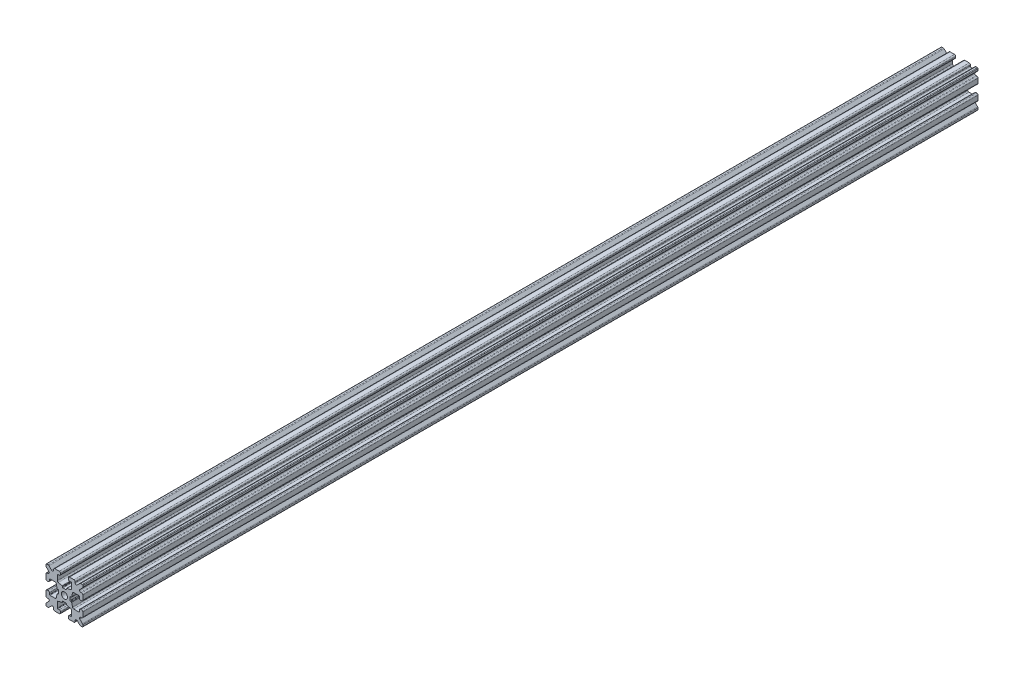
SolidWorks part; units mm, degrees
material "1060 Alloy"
ref_plane "Front Plane" through (0, 0, 0) normal (0, 0, 1) x (1, 0, 0)
ref_plane "Top Plane" through (0, 0, 0) normal (0, 1, 0) x (1, 0, 0)
ref_plane "Right Plane" through (0, 0, 0) normal (1, 0, 0) x (0, 0, -1)
sketch "Sketch1" plane through (0, 0, 0) normal (0, 0, 1) x (1, 0, 0)
  line L1 (-7.5, -7.5) -> (7.5, -7.5)
  line L2 (-7.5, -7.5) -> (-7.5, 7.5)
  line L3 (-7.5, 7.5) -> (7.5, 7.5)
  line L4 (7.5, -7.5) -> (7.5, 7.5)
  line L5 (-7.5, -7.5) -> (7.5, 7.5) construction
  line L6 (-7.5, 7.5) -> (7.5, -7.5) construction
  circle A0 centre (0, 0) radius 1.25
  point P0 (0, 0)
  dimension "D2" = 2.5
  dimension "D1" = 15
extrude "Boss-Extrude1" add sketch "Sketch1" along normal mid plane 365
fillet "Fillet1" radius 0.25 4 edges at (7.5, -7.5, 0) (-7.5, -7.5, 0) (7.5, 7.5, 0) (-7.5, 7.5, 0)
sketch "Sketch2" plane through (0, 0, 182.5) normal (0, 0, 1) x (1, 0, 0)
  line L0 (-7.5, 7.25) -> (-7.5, -7.25) construction
  line L1 (-7.5, 1.6) -> (-6.1, 1.6)
  line L2 (-7.5, 1.6) -> (-7.5, -1.6)
  line L3 (-7.5, -1.6) -> (-6.1, -1.6)
  line L4 (-6.1, 1.6) -> (-6.1, 2.9)
  line L5 (0, 0) -> (-12.1036, 0) construction
  line L6 (-6.1, -2.9) -> (-3.4, -2.9)
  line L7 (0, 0) -> (-7.25, 7.25) construction
  line L8 (-6.1, 2.9) -> (-3.4, 2.9)
  line L9 (-3.4, -2.9) -> (-3.4, 2.9)
  line L10 (55, 0) -> (-55, 0) construction
  line L11 (-6.1, -2.9) -> (-6.1, -1.6)
  line L12 (2.9, 6.1) -> (1.6, 6.1)
  line L13 (2.9, 3.4) -> (-2.9, 3.4)
  line L14 (-2.9, 6.1) -> (-2.9, 3.4)
  line L15 (2.9, 6.1) -> (2.9, 3.4)
  line L16 (-1.6, 6.1) -> (-2.9, 6.1)
  line L17 (1.6, 7.5) -> (1.6, 6.1)
  line L18 (-1.6, 7.5) -> (1.6, 7.5)
  line L19 (-1.6, 7.5) -> (-1.6, 6.1)
  line L20 (-1.6, -7.5) -> (-1.6, -6.1)
  line L21 (-1.6, -7.5) -> (1.6, -7.5)
  line L22 (1.6, -7.5) -> (1.6, -6.1)
  line L23 (-1.6, -6.1) -> (-2.9, -6.1)
  line L24 (2.9, -6.1) -> (2.9, -3.4)
  line L25 (-2.9, -6.1) -> (-2.9, -3.4)
  line L26 (2.9, -3.4) -> (-2.9, -3.4)
  line L27 (2.9, -6.1) -> (1.6, -6.1)
  line L28 (6.1, -2.9) -> (6.1, -1.6)
  line L29 (3.4, -2.9) -> (3.4, 2.9)
  line L30 (6.1, 2.9) -> (3.4, 2.9)
  line L31 (6.1, -2.9) -> (3.4, -2.9)
  line L32 (6.1, 1.6) -> (6.1, 2.9)
  line L33 (7.5, -1.6) -> (6.1, -1.6)
  line L34 (7.5, 1.6) -> (7.5, -1.6)
  line L35 (7.5, 1.6) -> (6.1, 1.6)
  dimension "D1" = 3.2
  dimension "D2" = 5.8
  dimension "D3" = 1.4
  dimension "D4" = 2.7
extrude "Cut-Extrude1" cut sketch "Sketch2" against normal through all
sketch "Sketch4" plane through (0, 0, 182.5) normal (0, 0, 1) x (1, 0, 0)
  line L0 (-3.4, 2.9) -> (-2.75, 0)
  line L1 (55, 0) -> (-55, 0) construction
  line L2 (-2.75, 0) -> (-3.4, -2.9)
  line L3 (-3.4, -2.9) -> (-3.4, 2.9) construction
  line L4 (-3.4, 2.9) -> (-3.4, -2.9)
  line L5 (-2.9, 3.4) -> (0, 2.75)
  line L6 (0, 2.75) -> (2.9, 3.4)
  line L7 (2.9, 3.4) -> (-2.9, 3.4)
  line L8 (3.4, 2.9) -> (2.75, 0)
  line L9 (2.75, 0) -> (3.4, -2.9)
  line L10 (3.4, -2.9) -> (3.4, 2.9)
  line L11 (-2.9, -3.4) -> (0, -2.75)
  line L12 (0, -2.75) -> (2.9, -3.4)
  line L13 (2.9, -3.4) -> (-2.9, -3.4)
  circle A2 centre (0, 0) radius 2.75
  circle A3 centre (0, 0) radius 2.75 construction
  dimension "D1" = 1.5
extrude "Cut-Extrude3" cut sketch "Sketch4" against normal through all
fillet "Fillet3" radius 0.5 16 edges at (-6.1, -1.6, 0) (-7.5, -1.6, 0) (-6.1, 1.6, 0) (-7.5, 1.6, 0) (-1.6, -7.5, 0) (-1.6, -6.1, 0) (1.6, -7.5, 0) (1.6, -6.1, 0) (6.1, -1.6, 0) (7.5, -1.6, 0) (7.5, 1.6, 0) (6.1, 1.6, 0) (1.6, 7.5, 0) (1.6, 6.1, 0) (-1.6, 7.5, 0) (-1.6, 6.1, 0)
fillet "Fillet4" radius 0.5 8 edges at (-3.4, 2.9, 0) (-3.4, -2.9, 0) (2.9, -3.4, 0) (-2.9, -3.4, 0) (3.4, -2.9, 0) (3.4, 2.9, 0) (-2.9, 3.4, 0) (2.9, 3.4, 0)
fillet "Fillet5" radius 3 4 edges at (0, -2.75, 0) (2.75, 0, 0) (-2.75, 0, 0) (0, 2.75, 0)
fillet "Fillet6" radius 0.2 8 edges at (-2.9, -6.1, 0) (2.9, -6.1, 0) (6.1, -2.9, 0) (6.1, 2.9, 0) (2.9, 6.1, 0) (-2.9, 6.1, 0) (-6.1, -2.9, 0) (-6.1, 2.9, 0)
sketch "Sketch5" plane through (0, 0, 182.5) normal (0, 0, 1) x (1, 0, 0)
  line L0 (0, 0) -> (-7.25, 7.25) construction
  line L1 (-7.5, 6.4393) -> (-5.4607, 4.4)
  line L2 (-6.4393, 7.5) -> (-4.4, 5.4607)
  line L3 (-7.5, 4.4) -> (-5.4607, 4.4)
  line L4 (-3.8003, 2.9) -> (-5.9, 2.9) construction
  line L5 (0, 0) -> (-12.1819, 0) construction
  line L6 (-4.4, 7.5) -> (-4.4, 5.4607)
  line L7 (-2.9, 5.9) -> (-2.9, 3.8003) construction
  line L8 (-7.5, 6.4393) -> (-7.5, 4.4)
  line L9 (-7.5, 7.25) -> (-7.5, 2.1) construction
  line L10 (2.1, -7.5) -> (7.25, -7.5) construction
  line L11 (7.5, -7.25) -> (7.5, -2.1) construction
  line L12 (7.25, 7.5) -> (2.1, 7.5) construction
  line L13 (-2.1, 7.5) -> (-7.25, 7.5) construction
  line L14 (-4.4, 7.5) -> (-6.4393, 7.5)
  line L16 (55, 0) -> (-55, 0) construction
  line L17 (0, 0) -> (0, 10.993) construction
  line L18 (0, -54.6431) -> (0, 54.6431) construction
  line L20 (4.4, 7.5) -> (6.4393, 7.5)
  line L22 (7.5, 6.4393) -> (7.5, 4.4)
  line L23 (4.4, 7.5) -> (4.4, 5.4607)
  line L24 (7.5, 4.4) -> (5.4607, 4.4)
  line L25 (6.4393, 7.5) -> (4.4, 5.4607)
  line L26 (7.5, 6.4393) -> (5.4607, 4.4)
  line L27 (7.5, -6.4393) -> (5.4607, -4.4)
  line L28 (6.4393, -7.5) -> (4.4, -5.4607)
  line L29 (7.5, -4.4) -> (5.4607, -4.4)
  line L30 (4.4, -7.5) -> (4.4, -5.4607)
  line L31 (7.5, -6.4393) -> (7.5, -4.4)
  line L33 (4.4, -7.5) -> (6.4393, -7.5)
  line L36 (-4.4, -7.5) -> (-6.4393, -7.5)
  line L38 (-7.5, -6.4393) -> (-7.5, -4.4)
  line L39 (-4.4, -7.5) -> (-4.4, -5.4607)
  line L40 (-7.5, -4.4) -> (-5.4607, -4.4)
  line L41 (-6.4393, -7.5) -> (-4.4, -5.4607)
  line L42 (-7.5, -6.4393) -> (-5.4607, -4.4)
  dimension "D1" = 1.5
  dimension "D2" = 1.5
  dimension "D3" = 1.5
extrude "Cut-Extrude4" cut sketch "Sketch5" against normal through all
fillet "Fillet8" radius 0.5 24 edges at (-5.4607, 4.4, 0) (-7.5, 4.4, 0) (-5.4607, -4.4, 0) (-7.5, -4.4, 0) (-4.4, -7.5, 0) (-4.4, -5.4607, 0) (4.4, -7.5, 0) (4.4, -5.4607, 0) (5.4607, -4.4, 0) (7.5, -4.4, 0) (7.5, 4.4, 0) (5.4607, 4.4, 0) (4.4, 5.4607, 0) (4.4, 7.5, 0) (-4.4, 5.4607, 0) (-4.4, 7.5, 0) (-6.4393, 7.5, 0) (-7.5, 6.4393, 0) (6.4393, 7.5, 0) (7.5, 6.4393, 0) (6.4393, -7.5, 0) (7.5, -6.4393, 0) (-6.4393, -7.5, 0) (-7.5, -6.4393, 0)
sketch "Sketch6" plane through (0, 0, 182.5) normal (0, 0, 1) x (1, 0, 0)
  line L0 (0, 0) -> (0, 11.013) construction
  line L1 (0.6561, 2.8971) -> (2.1235, 2.8971) construction
  line L2 (0, -54.6431) -> (0, 54.6431) construction
  line L3 (0, 0) -> (7.25, 7.25) construction
  line L4 (7.5, 0.8255) -> (7.5, -0.8255)
  line L5 (2.3471, 0.8255) -> (7.5, 0.8255)
  line L6 (0, 0) -> (12.4016, 0) construction
  line L7 (0.8255, -7.5) -> (-0.8255, -7.5)
  line L8 (2.3471, -0.8255) -> (2.3471, 0.8255)
  line L9 (0.8255, -2.3471) -> (0.8255, -7.5)
  line L10 (7.5, -0.8255) -> (2.3471, -0.8255)
  line L11 (-7.5, -0.8255) -> (-2.3471, -0.8255)
  line L12 (-2.3471, -0.8255) -> (-2.3471, 0.8255)
  line L13 (-0.8255, -2.3471) -> (0.8255, -2.3471)
  line L14 (-0.8255, 7.5) -> (-0.8255, 2.3471)
  line L15 (-0.8255, 2.3471) -> (0.8255, 2.3471)
  line L16 (-0.8255, -7.5) -> (-0.8255, -2.3471)
  line L17 (0.8255, 2.3471) -> (0.8255, 7.5)
  line L18 (0.8255, 7.5) -> (-0.8255, 7.5)
  line L19 (3.9, 7.5) -> (2.1, 7.5) construction
  line L20 (-2.3471, 0.8255) -> (-7.5, 0.8255)
  line L21 (-7.5, 0.8255) -> (-7.5, -0.8255)
  point P5 (0, -2.5973)
  point P7 (0, 2.5973)
  dimension "D3" = 0.55
  dimension "D1" = 1.651
extrude "Cut-Extrude5" cut sketch "Sketch6" against normal through all
fillet "Fillet10" radius 0.2 16 edges at (-2.935, 0.8255, 0) (-2.935, -0.8255, 0) (2.935, -0.8255, 0) (2.935, 0.8255, 0) (0.8255, 2.935, 0) (-0.8255, 2.935, 0) (-2.3471, 0.8255, 0) (-2.3471, -0.8255, 0) (0.8255, 2.3471, 0) (-0.8255, 2.3471, 0) (2.3471, 0.8255, 0) (2.3471, -0.8255, 0) (0.8255, -2.935, 0) (0.8255, -2.3471, 0) (-0.8255, -2.3471, 0) (-0.8255, -2.935, 0)
